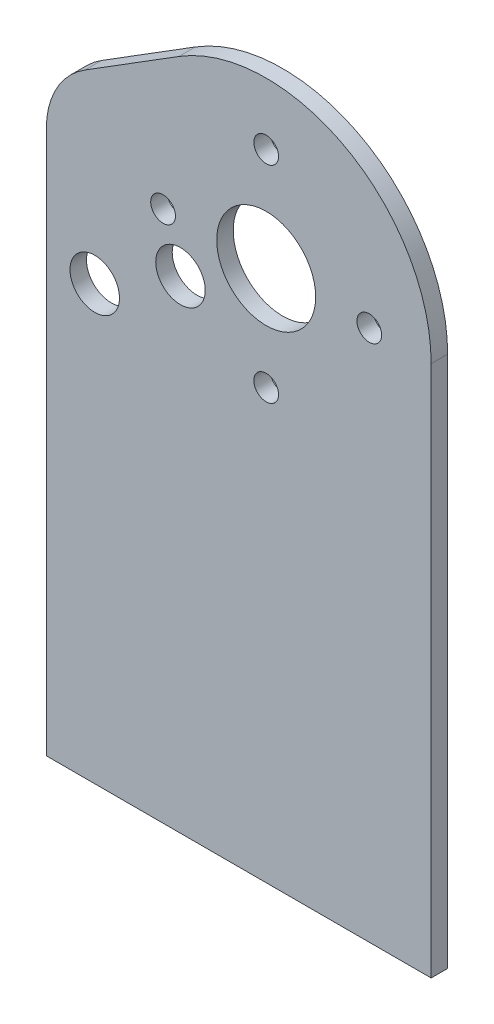
SolidWorks part; units mm, degrees
ref_plane "Front Plane" through (0, 0, 0) normal (0, 0, 1) x (1, 0, 0)
ref_plane "Top Plane" through (0, 0, 0) normal (0, 1, 0) x (1, 0, 0)
ref_plane "Right Plane" through (0, 0, 0) normal (1, 0, 0) x (0, 0, -1)
sketch "Sketch1" plane through (0, 0, 0) normal (0, 0, 1) x (1, 0, 0)
  line L0 (-10.598, 16.9612) -> (-21.9505, 9.8677)
  line L1 (-26.6515, -64.4943) -> (20, -64.4943)
  line L2 (-26.6515, -64.4943) -> (-26.6515, 1.3871)
  line L4 (20, -64.4943) -> (20, 0)
  arc A0 (20, 0) -> (-10.598, 16.9612) centre (0, 0) ccw
  arc A1 (-21.9505, 9.8677) -> (-26.6515, 1.3871) centre (-16.6515, 1.3871) ccw
  point P0 (0, 0)
  dimension "D1" = 40
  dimension "D2" = 10
extrude "Boss-Extrude1" add sketch "Sketch1" along normal blind 2
sketch "Sketch2" plane through (0, 0, 2) normal (0, 0, 1) x (1, 0, 0)
  circle A0 centre (0, 0) radius 6
  circle A1 centre (12.5, 0) radius 1.5
  circle A2 centre (0, -12.5) radius 1.5
  circle A3 centre (-12.5, 0) radius 1.5
  circle A4 centre (0, 12.5) radius 1.5
  dimension "D1" = 12
  dimension "D2" = 3
  dimension "D3" = 12.5
  dimension "D4" = 4
extrude "Cut-Extrude1" cut sketch "Sketch2" against normal blind 2
sketch "Sketch3" plane through (0, 0, 0) normal (0, 0, -1) x (-1, 0, 0)
  line L0 (0, 0) -> (10.3923, -6) construction
  line L1 (10.3923, -6) -> (20.7846, -12) construction
  line L2 (0, -1000) -> (0, 49000) construction
  circle A0 centre (10.3923, -6) radius 3
  circle A1 centre (20.7846, -12) radius 3
  dimension "D2" = 6
  dimension "D3" = 6
  dimension "D1" = 12
  dimension "D4" = 60
extrude "Cut-Extrude2" cut sketch "Sketch3" against normal blind 2
